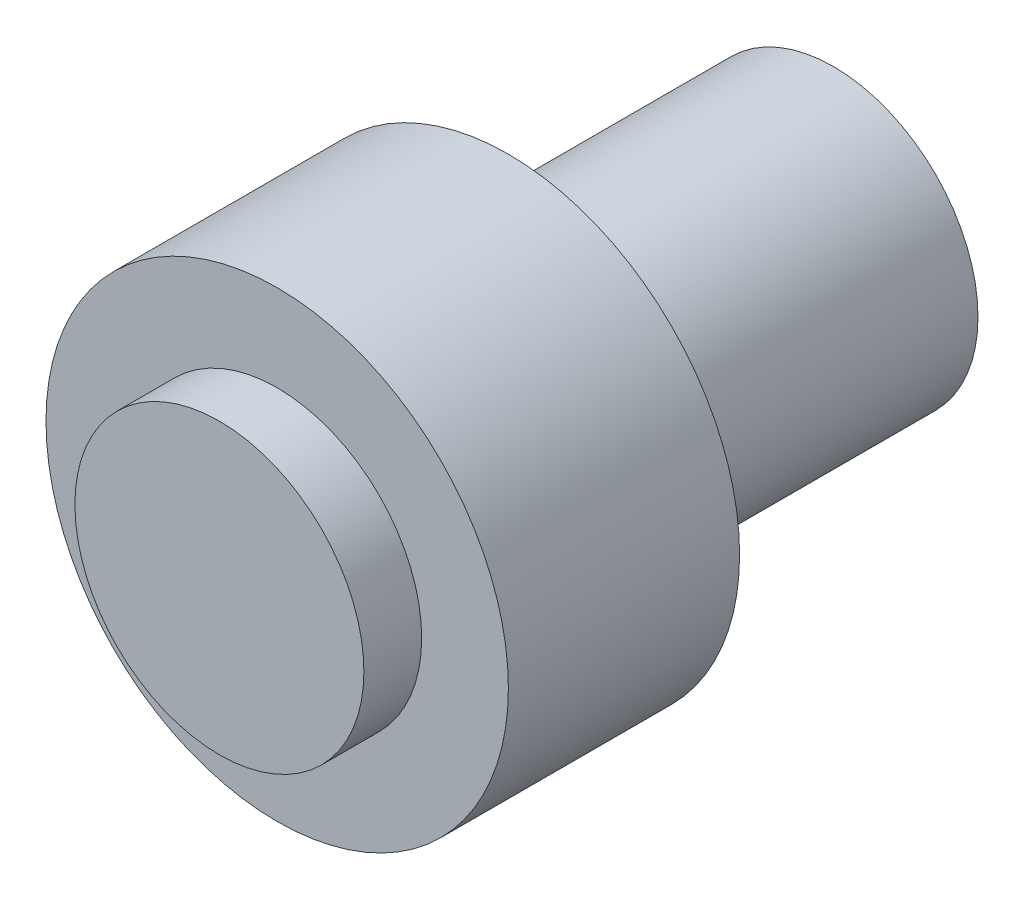
SolidWorks part; units mm, degrees
material "Stainless Steel (ferritic)"
ref_plane "Front Plane" through (0, 0, 0) normal (0, 0, 1) x (1, 0, 0)
ref_plane "Top Plane" through (0, 0, 0) normal (0, 1, 0) x (1, 0, 0)
ref_plane "Right Plane" through (0, 0, 0) normal (1, 0, 0) x (0, 0, -1)
sketch "Sketch1" plane through (0, 0, 0) normal (1, 0, 0) x (0, 0, -1)
  line L0 (0, 0) -> (26.9875, 0) construction
  line L1 (0, 0) -> (0, 10.16)
  line L2 (0, 10.16) -> (12.7, 10.16)
  line L3 (12.7, 10.16) -> (12.7, 6.35)
  line L4 (12.7, 6.35) -> (26.9875, 6.35)
  line L5 (26.9875, 6.35) -> (26.9875, 0)
  line L6 (0, 0) -> (26.9875, 0)
  dimension "D1" = 26.9875
  dimension "D2" = 6.35
  dimension "D3" = 10.16
  dimension "D4" = 12.7
revolve "Revolve1" add sketch "Sketch1" angle 360 about L0
sketch "Sketch2" plane through (0, 0, 0) normal (0, 0, 1) x (1, 0, 0)
  circle A0 centre (0, 0) radius 10.1953
  circle A1 centre (0, 0) radius 6.35
  dimension "D1" = 12.7
extrude "Cut-Extrude1" cut sketch "Sketch2" against normal blind 2.54
sketch "Sketch3" plane through (0, 0, 0) normal (0, 0, 1) x (1, 0, 0)
  circle A0 centre (0, 0) radius 6.35
